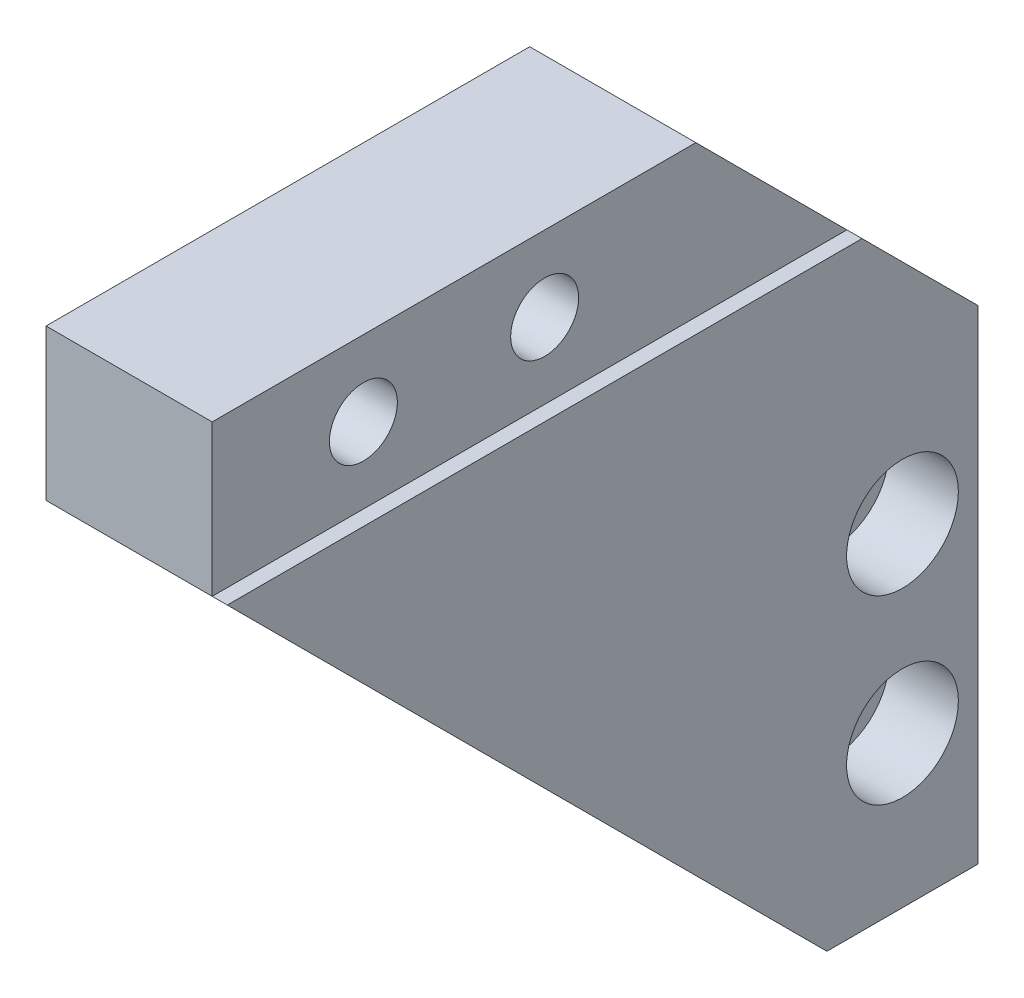
SolidWorks part; units mm, degrees
material "6061"
ref_plane "前视" through (0, 0, 0) normal (0, 0, 1) x (1, 0, 0)
ref_plane "上视" through (0, 0, 0) normal (0, 1, 0) x (1, 0, 0)
ref_plane "右视" through (0, 0, 0) normal (1, 0, 0) x (0, 0, -1)
sketch "草图1" plane through (0, 0, 0) normal (1, 0, 0) x (0, 0, -1)
  line L0 (0, 0) -> (42.0223, 0)
  line L1 (42.0223, 0) -> (59.7, -17.6777)
  line L2 (59.7, -17.6777) -> (59.7, -59.7)
  line L3 (59.7, -59.7) -> (0, 0)
  dimension "D1" = 59.7
  dimension "D2" = 25
extrude "凸台-拉伸1" add sketch "草图1" along normal mid plane 12
hole_wizard "打孔尺寸根据内六角圆柱头螺钉的类型3" positions "草图3" profile "草图2" counterbore size "M4" standard "Gb" end condition through all
sketch "草图3" plane through (0, 0, 0) normal (0, -0.7071, 0.7071) x (1, 0, 0)
  line L0 (0, -84.4285) -> (0, -42.2143) construction
  line L1 (6, -84.4285) -> (-6, -84.4285) construction
  line L2 (0, -42.2143) -> (6, -42.2143) construction
  line L3 (6, 0) -> (6, -84.4285) construction
  point P0 (0, -35.7143)
  point P14 (0, -48.7143)
  dimension "D1" = 13
sketch "草图2" plane through (0, -25.2538, -25.2538) normal (1, 0, 0) x (0, -0.7071, -0.7071)
  line L0 (0, 0) -> (0, 42.2143)
  line L1 (0, 42.2143) -> (2.25, 42.2143)
  line L3 (2.25, 42.2143) -> (2.25, 4.6)
  line L4 (2.25, 4.6) -> (4, 4.6)
  line L5 (4, 4.6) -> (4, 0)
  line L7 (4, 0) -> (0, 0)
  line L11 (0, -6.35) -> (0, 107.95) construction
  dimension "通孔孔直径" = 4.5
  dimension "通孔孔深度" = 42.2143
  dimension "柱形沉头孔直径" = 8
  dimension "柱形沉头孔深度" = 4.6
sketch "草图10" plane through (6, 0, 0) normal (-1, 0, 0) x (0, 0, 1)
  line L0 (-42.0223, 0) -> (0, 0)
  line L1 (0, 0) -> (-10, -10)
  line L2 (0, 0) -> (-59.7, -59.7) construction
  line L3 (-10, -10) -> (-52.0223, -10)
  line L4 (-59.7, -17.6777) -> (-42.0223, 0) construction
  line L5 (-52.0223, -10) -> (-42.0223, 0)
  dimension "D1" = 10
extrude "切除-拉伸1" cut sketch "草图10" along normal blind 1
sketch "草图11" plane through (-6, 0, 0) normal (-1, 0, 0) x (0, 0, 1)
  line L0 (-59.7, -17.6777) -> (-59.7, -59.7)
  line L1 (-59.7, -59.7) -> (-49.7, -49.7)
  line L2 (0, 0) -> (-59.7, -59.7) construction
  line L3 (-49.7, -49.7) -> (-49.7, -7.6777)
  line L4 (-59.7, -17.6777) -> (-42.0223, 0) construction
  line L5 (-49.7, -7.6777) -> (-59.7, -17.6777)
  dimension "D1" = 10
extrude "切除-拉伸2" cut sketch "草图11" against normal blind 1
hole_wizard "打孔尺寸根据内六角圆柱头螺钉的类型2" positions "草图13" profile "草图12" counterbore size "M4" standard "Gb" end condition through all
sketch "草图13" plane through (-6, 0, 0) normal (-1, 0, 0) x (0, 0, 1)
  line L0 (-21.0112, 0) -> (-31.0112, -10) construction
  line L1 (-42.0223, 0) -> (0, 0) construction
  line L3 (-52.0223, -10) -> (-10, -10) construction
  line L4 (-26.0112, -5) -> (-13.3274, -5) construction
  line L5 (-26.0112, -5) -> (-26.0112, 3.9601) construction
  point P0 (-20.0112, -5)
  point P21 (-32.0112, -5)
  dimension "D1" = 12
sketch "草图12" plane through (-6, -5, -20.0112) normal (0, 1, 0) x (0, 0, 1)
  line L0 (0, 0) -> (0, 12)
  line L1 (0, 12) -> (2.25, 12)
  line L3 (2.25, 12) -> (2.25, 4.6)
  line L4 (2.25, 4.6) -> (3.7, 4.6)
  line L5 (3.7, 4.6) -> (3.7, 0)
  line L7 (3.7, 0) -> (0, 0)
  line L11 (0, -6.35) -> (0, 107.95) construction
  dimension "通孔孔直径" = 4.5
  dimension "通孔孔深度" = 12
  dimension "柱形沉头孔直径" = 7.4
  dimension "柱形沉头孔深度" = 4.6
hole_wizard "打孔尺寸根据内六角圆柱头螺钉的类型3" positions "草图15" profile "草图14" counterbore size "M4" standard "Gb" end condition through all
sketch "草图15" plane through (6, 0, 0) normal (1, 0, 0) x (0, 0, -1)
  line L0 (59.7, -38.6888) -> (49.7, -28.6888) construction
  line L1 (59.7, -59.7) -> (59.7, -17.6777) construction
  line L2 (49.7, -49.7) -> (49.7, -7.6777) construction
  line L3 (54.7, -33.6888) -> (54.7, -40.3388) construction
  line L4 (54.7, -33.6888) -> (60.3618, -33.6888) construction
  point P0 (54.7, -39.6888)
  point P19 (54.7, -27.6888)
  dimension "D1" = 12
sketch "草图14" plane through (6, -39.6888, -54.7) normal (0, 1, 0) x (0, 0, -1)
  line L0 (0, 0) -> (0, 12)
  line L1 (0, 12) -> (2.25, 12)
  line L3 (2.25, 12) -> (2.25, 4.6)
  line L4 (2.25, 4.6) -> (3.7, 4.6)
  line L5 (3.7, 4.6) -> (3.7, 0)
  line L7 (3.7, 0) -> (0, 0)
  line L11 (0, -6.35) -> (0, 107.95) construction
  dimension "通孔孔直径" = 4.5
  dimension "通孔孔深度" = 12
  dimension "柱形沉头孔直径" = 7.4
  dimension "柱形沉头孔深度" = 4.6
sketch "草图16" plane through (6, 0, 0) normal (1, 0, 0) x (0, 0, -1)
  line L0 (10, -10) -> (10, 0)
  line L1 (0, 0) -> (42.0223, 0) construction
  line L2 (10, 0) -> (0, 0)
  line L3 (0, 0) -> (10, -10)
  line L4 (59.7, -59.7) -> (59.7, -49.7)
  line L5 (59.7, -59.7) -> (59.7, -17.6777) construction
  line L6 (59.7, -49.7) -> (49.7, -49.7)
  line L7 (49.7, -49.7) -> (59.7, -59.7)
extrude "切除-拉伸3" cut sketch "草图16" against normal through all
